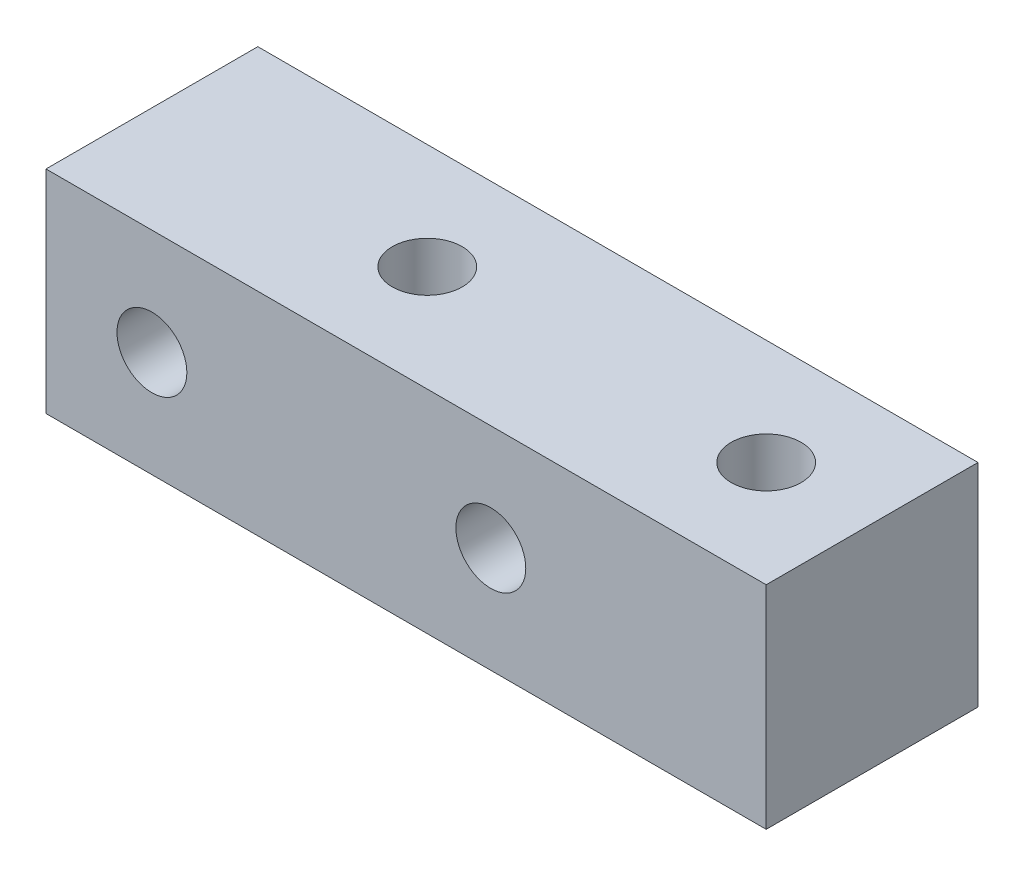
SolidWorks part; units mm, degrees
material "6061 合金"
ref_plane "前视基准面" through (0, 0, 0) normal (0, 0, 1) x (1, 0, 0)
ref_plane "上视基准面" through (0, 0, 0) normal (0, 1, 0) x (1, 0, 0)
ref_plane "右视基准面" through (0, 0, 0) normal (1, 0, 0) x (0, 0, -1)
sketch "草图1" plane through (0, 0, 0) normal (0, 0, 1) x (1, 0, 0)
  line L1 (17, -5) -> (-17, -5)
  line L2 (17, -5) -> (17, 5)
  line L3 (17, 5) -> (-17, 5)
  line L4 (-17, -5) -> (-17, 5)
  line L5 (17, -5) -> (-17, 5) construction
  line L6 (17, 5) -> (-17, -5) construction
  point P0 (0, 0)
  dimension "D1" = 34
  dimension "D2" = 10
extrude "凸台-拉伸1" add sketch "草图1" along normal blind 10
sketch "草图2" plane through (0, 0, 10) normal (0, 0, 1) x (1, 0, 0)
  line L0 (-17, 5) -> (-17, -5) construction
  point P0 (-12, 0)
  point P1 (4, 0)
  dimension "D1" = 5
  dimension "D2" = 16
sketch "草图3" plane through (0, 5, 0) normal (0, 1, 0) x (1, 0, 0)
  line L0 (17, -10) -> (17, 0) construction
  point P0 (-4, -5)
  point P1 (12, -5)
  dimension "D1" = 5
  dimension "D2" = 16
hole_wizard "M4 螺纹孔的螺纹孔钻头1" positions "3D草图1" profile "草图4" hole size "M4" standard "DIN" end condition through all
sketch3d "3D草图1"
  point P0 (-4, 5, 5)
  point P3 (12, 5, 5)
  point P6 (4, 0, 10)
  point P9 (-12, 0, 10)
sketch "草图4" plane through (-4, 5, 5) normal (1, 0, 0) x (0, 0, 1)
  line L0 (0, 0) -> (0, 10)
  line L1 (0, 10) -> (1.65, 10)
  line L2 (1.65, 10) -> (1.65, 0)
  line L5 (1.65, 0) -> (0, 0)
  line L11 (0, -6.35) -> (0, 107.95) construction
  dimension "通孔孔直径" = 3.3
  dimension "通孔孔深度" = 10
